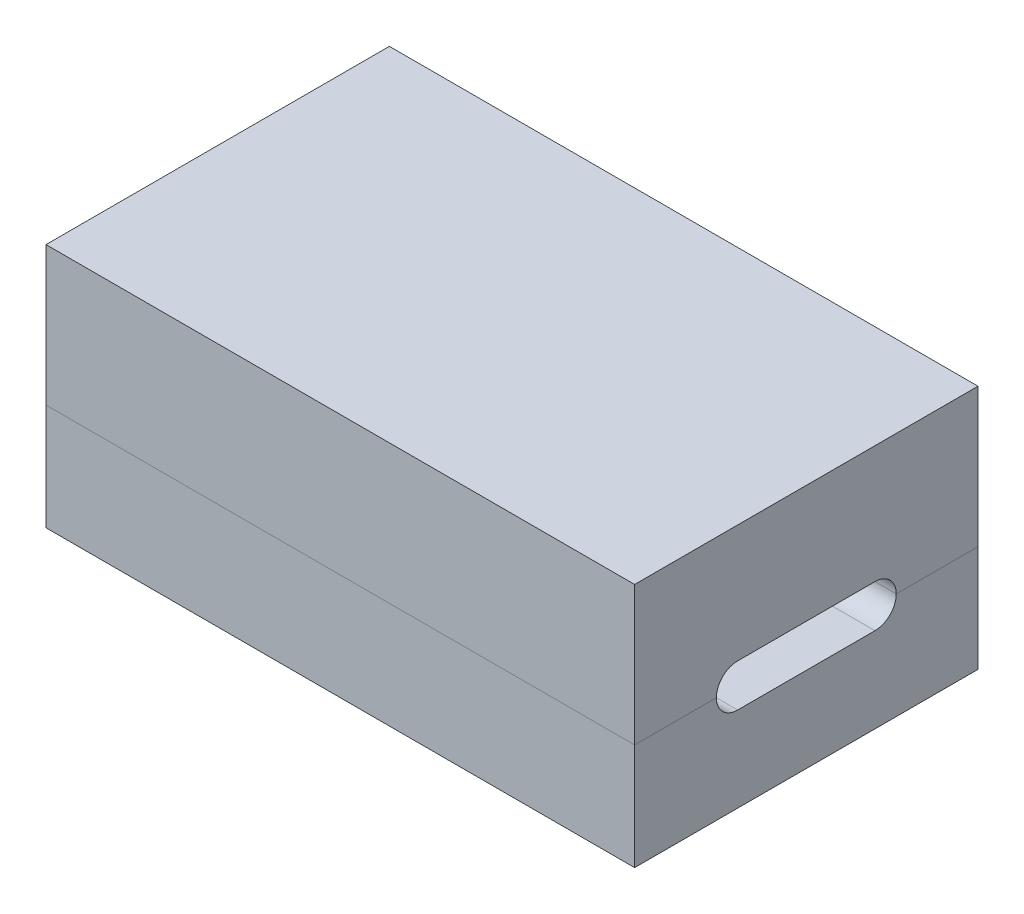
SolidWorks part; units mm, degrees
ref_plane "Front Plane" through (0, 0, 0) normal (0, 0, 1) x (1, 0, 0)
ref_plane "Top Plane" through (0, 0, 0) normal (0, 1, 0) x (1, 0, 0)
ref_plane "Right Plane" through (0, 0, 0) normal (1, 0, 0) x (0, 0, -1)
sketch "Sketch1" plane through (0, 0, 0) normal (0, 1, 0) x (1, 0, 0)
  line L1 (-18, 10.5) -> (18, 10.5)
  line L2 (-18, 10.5) -> (-18, -10.5)
  line L3 (-18, -10.5) -> (18, -10.5)
  line L4 (18, 10.5) -> (18, -10.5)
  line L5 (-18, 10.5) -> (18, -10.5) construction
  line L6 (-18, -10.5) -> (18, 10.5) construction
  point P0 (0, 0)
  dimension "D1" = 21
  dimension "D2" = 36
extrude "Boss-Extrude2" add sketch "Sketch1" along normal blind 15
sketch "Sketch2" plane through (18, 0, 0) normal (1, 0, 0) x (0, 0, -1)
  line L0 (-4.2, 6.5) -> (4.2, 6.5) construction
  line L1 (-4.2, 7.8) -> (4.2, 7.8)
  line L2 (-4.2, 5.2) -> (4.2, 5.2)
  line L4 (10.5, 15) -> (10.5, 0) construction
  line L5 (-10.5, 0) -> (10.5, 0) construction
  arc A0 (-4.2, 7.8) -> (-4.2, 5.2) centre (-4.2, 6.5) ccw
  arc A1 (4.2, 5.2) -> (4.2, 7.8) centre (4.2, 6.5) ccw
  point P2 (0, 6.5)
  dimension "D1" = 10.5
  dimension "D2" = 6.5
  dimension "D3" = 8.4
  dimension "D4" = 1.3
extrude "Cut-Extrude1" cut sketch "Sketch2" against normal blind 15
ref_plane "Plane2" through (0, 6.5, 0) normal (0, 1, 0) x (1, 0, 0)
split "Split1" trim tools "Plane2" bodies to split 103 resulting bodies 104 105
sketch "Sketch5" plane through (0, 6.5, 0) normal (0, 1, 0) x (1, 0, 0)
  line L0 (-18, 10.5) -> (-18, -10.5) construction
  line L1 (-15, 7.5) -> (15, 7.5)
  line L2 (-15, 7.5) -> (-15, -7.5)
  line L3 (-15, -7.5) -> (15, -7.5)
  line L4 (15, 7.5) -> (15, -7.5)
  line L5 (18, 5.5) -> (18, 10.5) construction
  line L6 (18, 10.5) -> (-18, 10.5) construction
  line L7 (-18, -10.5) -> (18, -10.5) construction
  dimension "D1" = 3
  dimension "D2" = 3
  dimension "D3" = 3
  dimension "D4" = 3
extrude "Cut-Extrude2" cut sketch "Sketch5" against normal blind 3.5
sketch "Sketch7" plane through (0, 6.5, 0) normal (0, -1, 0) x (1, 0, 0)
  line L0 (-18, -10.5) -> (-18, 10.5) construction
  line L1 (-15, 7.5) -> (15, 7.5)
  line L2 (-15, 7.5) -> (-15, -7.5)
  line L3 (-15, -7.5) -> (15, -7.5)
  line L4 (15, 7.5) -> (15, -7.5)
  line L5 (18, 10.5) -> (18, 5.5) construction
  line L6 (-18, 10.5) -> (18, 10.5) construction
  line L7 (18, -10.5) -> (-18, -10.5) construction
  dimension "D1" = 3
  dimension "D2" = 3
  dimension "D3" = 3
  dimension "D4" = 3
extrude "Cut-Extrude3" cut sketch "Sketch7" against normal blind 5.5
